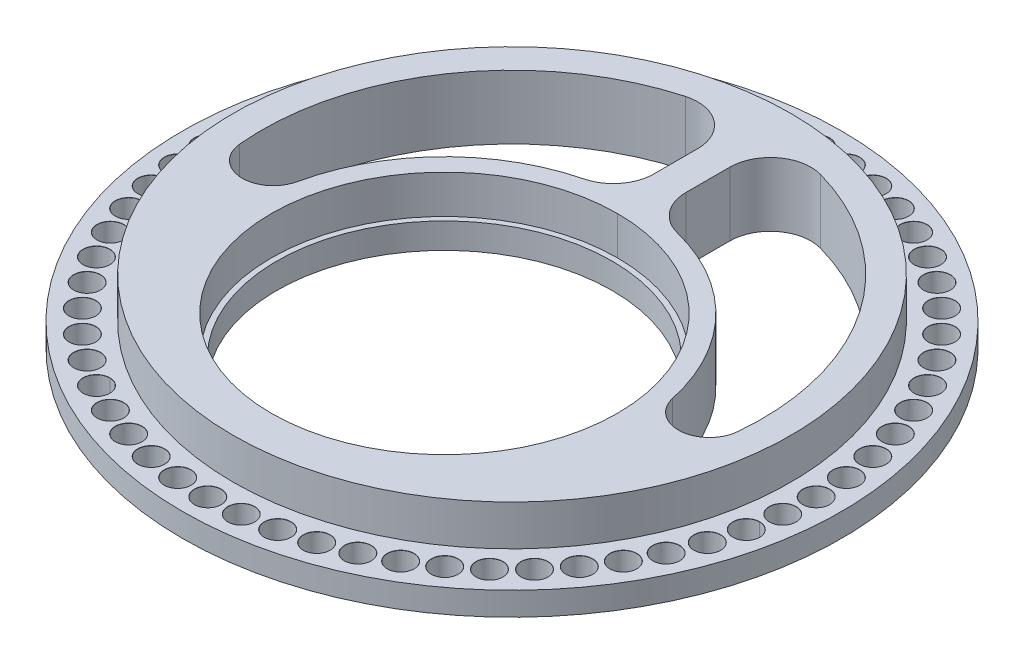
SolidWorks part; units mm, degrees
material "6061-T6 (SS)"
ref_plane "X-Y Datum" through (0, 0, 0) normal (0, 0, 1) x (1, 0, 0)
ref_plane "X-Z Datum" through (0, 0, 0) normal (0, 1, 0) x (1, 0, 0)
ref_plane "Y-Z Datum" through (0, 0, 0) normal (1, 0, 0) x (0, 0, -1)
sketch "Sketch1" plane through (0, 0, 0) normal (0, 1, 0) x (1, 0, 0)
  line L0 (0, 0) -> (0, -12.7) construction
  line L1 (0, -43.0151) -> (0, 43.0151) construction
  line L2 (0, 52.3875) -> (0, 61.9125) construction
  circle A0 centre (0, -12.7) radius 30.988
  circle A1 centre (0, 0) radius 52.3875 construction
  circle A2 centre (0, 0) radius 61.9125
  circle A3 centre (0, 0) radius 57.15 construction
  point P12 (0, 57.15)
  dimension "D2" = 61.976
  dimension "D3" = 104.775
  dimension "D4" = 123.825
  dimension "D5" = 114.3
  dimension "D1" = 12.7
extrude "Slotted-Body Extrude" add sketch "Sketch1" along normal blind 4.191 and the other way blind 0.2032
sketch "Sketch5" plane through (0, 4.191, 0) normal (0, 1, 0) x (1, 0, 0)
  circle A0 centre (0, 0) radius 52.3875 construction
  circle A1 centre (0, 0) radius 52.3875
extrude "Boss-Extrude3" add sketch "Sketch5" along normal blind 7.62
sketch "Sketch6" plane through (0, -0.2032, 0) normal (0, -1, 0) x (1, 0, 0)
  line L0 (0, -79.2756) -> (0, 0) construction
  line L2 (3.014, -37.9067) -> (3.014, -29.6741)
  line L4 (-3.014, -37.9067) -> (-3.014, -29.6741)
  circle A0 centre (0, 12.7) radius 30.988 construction
  circle A1 centre (0, 12.7) radius 30.988 construction
  circle A2 centre (0, 12.7) radius 32.512
  arc A9 (-35.2562, 5.0907) -> (-8.7792, -22.2832) centre (0, 12.7) ccw
  arc A10 (-46.783, 4.406) -> (-12.6921, -45.2435) centre (0, 0) ccw
  arc A11 (-46.783, 4.406) -> (-35.2562, 5.0907) centre (-40.9667, 3.8583) cw
  arc A19 (-3.014, -29.6741) -> (-8.7792, -22.2832) centre (-10.634, -29.6741) ccw
  arc A20 (-3.014, -37.9067) -> (-12.6921, -45.2435) centre (-10.634, -37.9067) cw
  circle A21 centre (0, 0) radius 61.9125 construction
  arc A27 (46.783, 4.406) -> (35.2562, 5.0907) centre (40.9667, 3.8583) ccw
  arc A28 (46.783, 4.406) -> (12.6921, -45.2435) centre (0, 0) cw
  arc A29 (3.014, -37.9067) -> (12.6921, -45.2435) centre (10.634, -37.9067) ccw
  arc A30 (3.014, -29.6741) -> (8.7792, -22.2832) centre (10.634, -29.6741) cw
  arc A31 (35.2562, 5.0907) -> (8.7792, -22.2832) centre (0, 12.7) cw
  point P30 (0, 0)
  point P31 (-3.014, -23.2419)
  point P32 (0, 0)
  point P36 (-3.014, -46.8932)
  dimension "D1" = 65.024
  dimension "D2" = 7.62
  dimension "D3" = 5.842
  dimension "D4" = 46.99
  dimension "D5" = 7.62
  dimension "D6" = 36.068
  dimension "D8" = 8.2326
extrude "Cut-Extrude5" cut sketch "Sketch6" against normal through all
sketch "Sketch8" plane through (0, -0.2032, 0) normal (0, -1, 0) x (1, 0, 0)
  circle A0 centre (0, 12.7) radius 32.512 construction
  circle A1 centre (0, 12.7) radius 32.512
  circle A2 centre (0, 12.7) radius 31.496
  dimension "D1" = 62.992
extrude "Boss-Extrude4" add sketch "Sketch8" against normal blind 4.795 separate body
hole_wizard "Ø5.0mm Dowel Hole2" positions "Sketch9" profile "Sketch10" hole size "Ø5.0" standard "ANSI Metric" end condition through all
sketch "Sketch9" plane through (0, 4.191, 0) normal (0, 1, 0) x (1, 0, 0)
  point P0 (0, 57.15)
sketch "Sketch10" plane through (0, 4.191, -57.15) normal (1, 0, 0) x (0, 0, 1)
  line L0 (0, 0) -> (0, 4.3942)
  line L1 (0, 4.3942) -> (2.5, 4.3942)
  line L2 (2.5, 4.3942) -> (2.5, 0.025)
  line L3 (2.5, 0.025) -> (2.525, 0)
  line L5 (2.525, 0) -> (0, 0)
  line L6 (-2.5, 0.025) -> (-2.525, 0) construction
  line L11 (0, -6.35) -> (0, 107.95) construction
  dimension "Thru Hole Dia." = 5
  dimension "Thru Hole Depth" = 4.3942
  dimension "Near C'Sink Dia." = 5.05
  dimension "Near C'Sink Angle" = 90
pattern_circular "CirPattern1" count 60 over 360 about axis through (0, 0, 0) along (0, 1, 0) of "Ø5.0mm Dowel Hole2"
ref_point "Point1"
ref_plane "Plane1" through (0, 0, 0) normal (1, 0, 0) x (0, 0, -1)
split line "Split Line1"
ref_point "Point2"
ref_point "Point3"
ref_point "Point4"
ref_point "Point5"
split line "Split Line2"
split line "Split Line3"
ref_plane "Plane2" through (-42.4707, 0, 0) normal (-1, 0, 0) x (0, 0, 1)
ref_plane "Plane3" through (55.9011, 0, 0) normal (-1, 0, 0) x (0, 0, 1)
split line "Split Line4"
split line "Split Line5"
sketch "Sketch11" plane through (0, -0.2032, 0) normal (0, -1, 0) x (1, 0, 0)
  line L1 (-61.9125, -61.9125) -> (61.9125, -61.9125)
  line L2 (-61.9125, -61.9125) -> (-61.9125, 61.9125)
  line L3 (-61.9125, 61.9125) -> (61.9125, 61.9125)
  line L4 (61.9125, -61.9125) -> (61.9125, 61.9125)
  line L5 (-61.9125, -61.9125) -> (61.9125, 61.9125) construction
  line L6 (-61.9125, 61.9125) -> (61.9125, -61.9125) construction
  circle A0 centre (0, 0) radius 61.9125 construction
  point P0 (0, 0)
